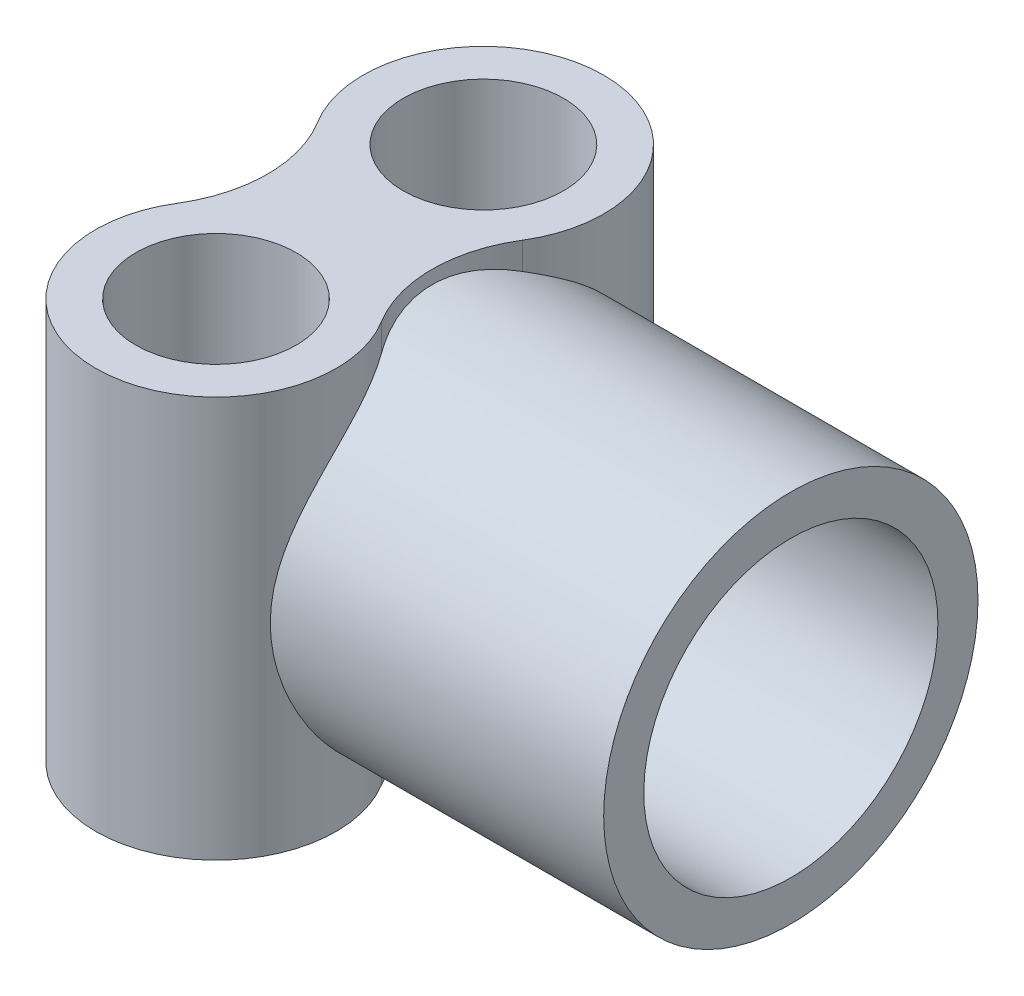
SolidWorks part; units mm, degrees
ref_plane "Front Plane" through (0, 0, 0) normal (0, 0, 1) x (1, 0, 0)
ref_plane "Top Plane" through (0, 0, 0) normal (0, 1, 0) x (1, 0, 0)
ref_plane "Right Plane" through (0, 0, 0) normal (1, 0, 0) x (0, 0, -1)
sketch "Sketch1" plane through (0, 0, 0) normal (0, 1, 0) x (1, 0, 0)
  line L0 (0, -10) -> (0, 10) construction
  circle A0 centre (0, 10) radius 6
  circle A1 centre (0, -10) radius 6
  arc A2 (7.6526, 5.2632) -> (-7.6526, 5.2632) centre (0, 10) ccw
  arc A3 (-7.6526, -5.2632) -> (7.6526, -5.2632) centre (0, -10) ccw
  arc A4 (7.6526, 5.2632) -> (7.6526, -5.2632) centre (16.1555, 0) ccw
  arc A5 (-7.6526, -5.2632) -> (-7.6526, 5.2632) centre (-16.1555, 0) ccw
  circle A6 centre (0, 10) radius 9 construction
  circle A7 centre (0, -10) radius 9 construction
  dimension "D1" = 12
  dimension "D2" = 12
  dimension "D4" = 3
  dimension "D5" = 3
  dimension "D6" = 20
  dimension "D7" = 20
  dimension "D3" = 20
extrude "Boss-Extrude1" add sketch "Sketch1" along normal blind 30
ref_plane "Plane1" through (10, 0, 0) normal (1, 0, 0) x (0, 0, -1)
sketch "Sketch2" plane through (10, 0, 0) normal (1, 0, 0) x (0, 0, -1)
  line L0 (0, 30) -> (0, 0) construction
  line L1 (5.2632, 30) -> (-5.2632, 30) construction
  line L2 (-5.2632, 0) -> (5.2632, 0) construction
  circle A0 centre (0, 15) radius 11
  circle A1 centre (0, 15) radius 14
  dimension "D1" = 22
  dimension "D2" = 3
extrude "Boss-Extrude2" add sketch "Sketch2" against normal blind 4 and the other way blind 23
